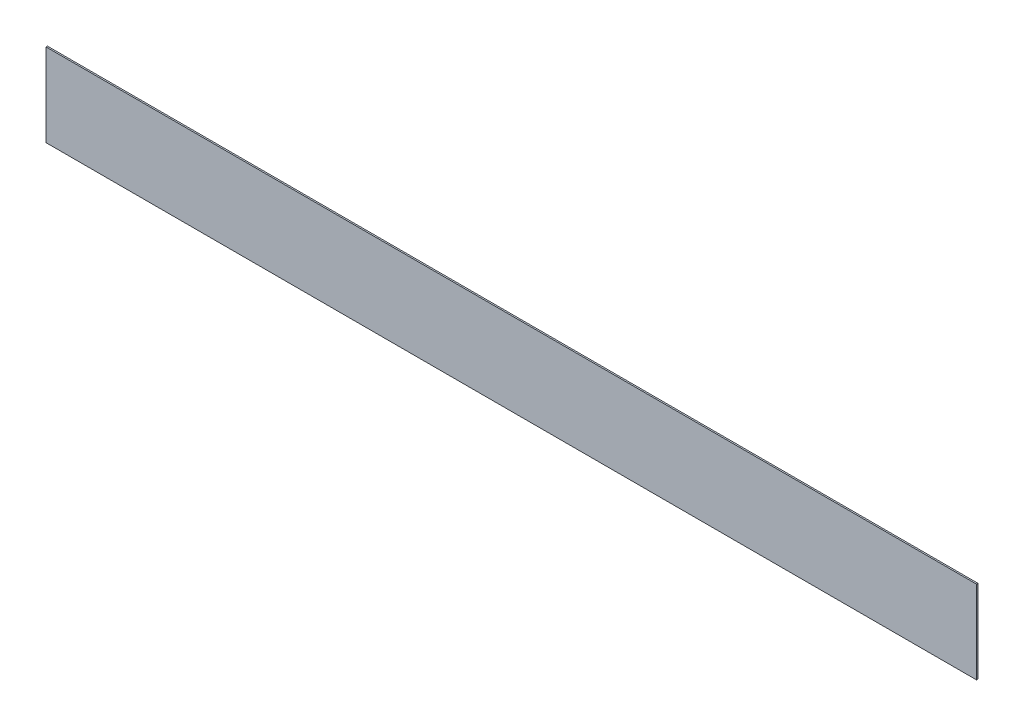
SolidWorks part; units mm, degrees
ref_plane "Front Plane" through (0, 0, 0) normal (0, 0, 1) x (1, 0, 0)
ref_plane "Top Plane" through (0, 0, 0) normal (0, 1, 0) x (1, 0, 0)
ref_plane "Right Plane" through (0, 0, 0) normal (1, 0, 0) x (0, 0, -1)
sketch "Sketch1" plane through (0, 0, 0) normal (0, 0, 1) x (1, 0, 0)
  line L1 (0, 0) -> (813, 0)
  line L2 (0, 0) -> (0, 72.46)
  line L3 (0, 72.46) -> (813, 72.46)
  line L4 (813, 0) -> (813, 72.46)
  dimension "D1" = 72.46
  dimension "D2" = 813
extrude "Boss-Extrude1" add sketch "Sketch1" along normal blind 1.27
